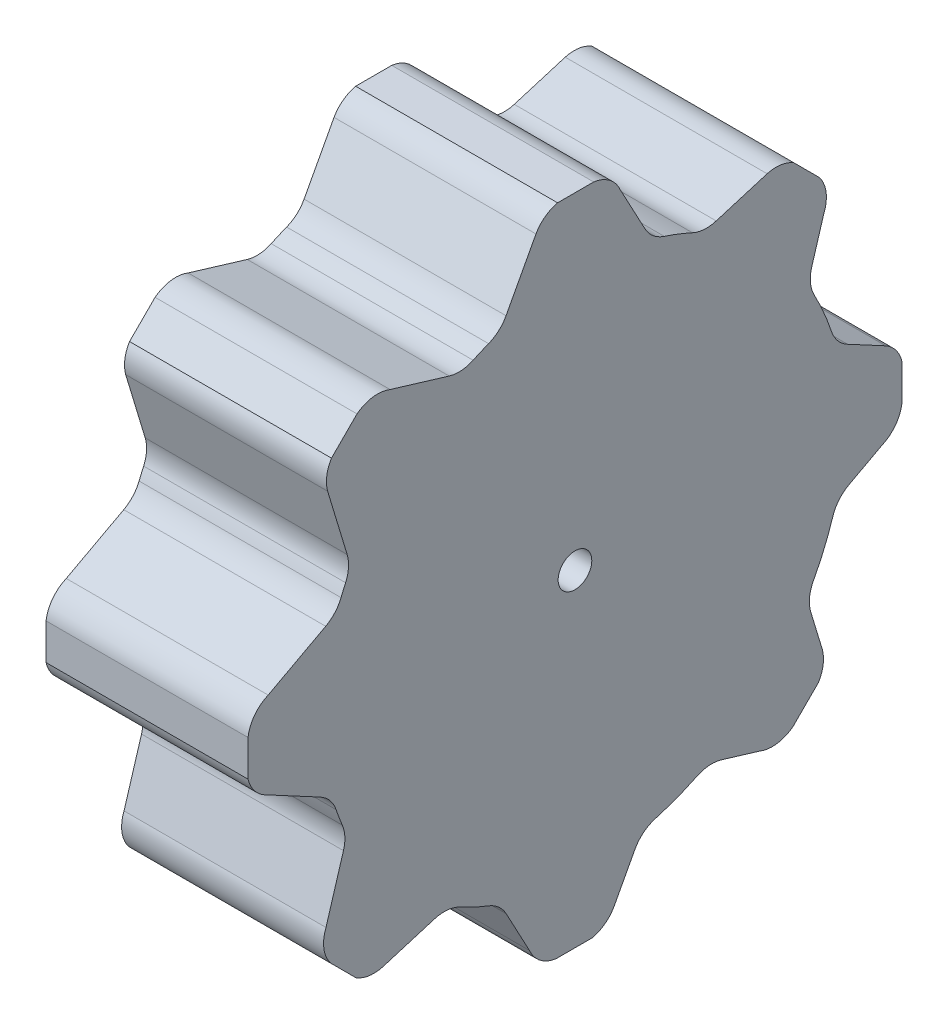
SolidWorks part; units mm, degrees
ref_plane "Front Plane" through (0, 0, 0) normal (0, 0, 1) x (1, 0, 0)
ref_plane "Top Plane" through (0, 0, 0) normal (0, 1, 0) x (1, 0, 0)
ref_plane "Right Plane" through (0, 0, 0) normal (1, 0, 0) x (0, 0, -1)
sketch "Sketch2" plane through (0, 0, 0) normal (1, 0, 0) x (0, 0, -1)
  line L4 (30.0857, -11.1861) -> (21.5417, -15.7633)
  line L5 (18.545, -19.7204) -> (18.545, -25.0855)
  line L6 (29.2555, -32.7457) -> (20.9479, -28.2952)
  line L7 (48.4288, 11.8388) -> (39.6545, 14.4915)
  line L11 (33.2739, -3.5445) -> (30.3732, 6.05)
  line L12 (34.7375, 13.8123) -> (30.9437, 10.0186)
  line L13 (77.5255, 16.2265) -> (73.8555, 23.0772)
  line L14 (56.8788, 15.3739) -> (61.3237, 23.671)
  line L15 (69.8985, 26.0738) -> (64.5333, 26.0738)
  line L16 (102.2913, -1.0523) -> (104.1103, 4.9644)
  line L17 (88.1041, 11.9586) -> (95.6688, 14.2456)
  line L18 (103.4312, 9.8814) -> (99.6374, 13.6751)
  line L19 (107.8316, -31.8426) -> (112.696, -29.2367)
  line L20 (107.6145, -13.6645) -> (113.2898, -16.7048)
  line L21 (115.6926, -25.2796) -> (115.6926, -19.9145)
  line L22 (88.8853, -57.7689) -> (94.5832, -59.4915)
  line L23 (102.1519, -45.3854) -> (103.8644, -51.05)
  line L24 (99.5002, -58.8123) -> (103.2939, -55.0186)
  line L25 (56.8883, -61.5554) -> (60.3821, -68.0772)
  line L26 (76.026, -62.8619) -> (72.914, -68.671)
  line L27 (64.3392, -71.0738) -> (69.7044, -71.0738)
  line L28 (32.7253, -41.3712) -> (30.1273, -49.9644)
  line L29 (46.2471, -56.9243) -> (38.5688, -59.2456)
  line L30 (30.8065, -54.8814) -> (34.6002, -58.6751)
  arc A2 (21.5417, -15.7633) -> (18.545, -19.7204) centre (23.5037, -20.3623) ccw
  arc A3 (18.545, -25.0855) -> (20.9479, -28.2952) centre (23.4133, -23.9453) ccw
  arc A5 (33.0415, -7.0564) -> (32.3654, -8.6398) centre (68.396, -23.0889) ccw
  arc A6 (39.6545, 14.4915) -> (34.7375, 13.8123) centre (37.7899, 9.8522) ccw
  arc A7 (30.9437, 10.0186) -> (30.3732, 6.05) centre (35.1924, 7.3825) ccw
  arc A8 (73.8555, 23.0772) -> (69.8985, 26.0738) centre (69.2566, 21.1152) ccw
  arc A9 (64.5333, 26.0738) -> (61.3237, 23.671) centre (65.6736, 21.2055) ccw
  arc A10 (104.1103, 4.9644) -> (103.4312, 9.8814) centre (99.471, 6.829) ccw
  arc A11 (99.6374, 13.6751) -> (95.6688, 14.2456) centre (97.0014, 9.4264) ccw
  arc A12 (112.696, -29.2367) -> (115.6926, -25.2796) centre (110.734, -24.6377) ccw
  arc A13 (115.6926, -19.9145) -> (113.2898, -16.7048) centre (110.8244, -21.0547) ccw
  arc A14 (94.5832, -59.4915) -> (99.5002, -58.8123) centre (96.4478, -54.8522) ccw
  arc A15 (103.2939, -55.0186) -> (103.8644, -51.05) centre (99.0453, -52.3825) ccw
  arc A16 (60.3821, -68.0772) -> (64.3392, -71.0738) centre (64.9811, -66.1152) ccw
  arc A17 (69.7044, -71.0738) -> (72.914, -68.671) centre (68.5641, -66.2055) ccw
  arc A18 (30.1273, -49.9644) -> (30.8065, -54.8814) centre (34.7666, -51.829) ccw
  arc A19 (34.6002, -58.6751) -> (38.5688, -59.2456) centre (37.2363, -54.4264) ccw
  arc A20 (54.2884, 13.0768) -> (51.989, 12.0934) centre (68.396, -23.0889) ccw
  arc A21 (84.5735, 12.1995) -> (80.3883, 13.8322) centre (68.396, -23.0889) ccw
  arc A22 (105.2312, -10.8354) -> (102.6637, -4.8486) centre (68.396, -23.0889) ccw
  arc A23 (102.5402, -41.5594) -> (105.4236, -34.7483) centre (68.396, -23.0889) ccw
  arc A24 (79.0599, -60.4154) -> (85.2656, -58.0517) centre (68.396, -23.0889) ccw
  arc A25 (50.0562, -57.3035) -> (54.2969, -59.2579) centre (68.396, -23.0889) ccw
  arc A26 (31.6299, -35.5483) -> (32.5555, -38.0033) centre (68.396, -23.0889) ccw
  arc A27 (29.2555, -32.7457) -> (31.6299, -35.5483) centre (26.8944, -37.1531) cw
  arc A28 (32.7253, -41.3712) -> (32.5555, -38.0033) centre (27.9392, -39.9243) ccw
  arc A29 (46.2471, -56.9243) -> (50.0562, -57.3035) centre (47.6941, -61.7103) cw
  arc A30 (56.8883, -61.5554) -> (54.2969, -59.2579) centre (52.4809, -63.9165) ccw
  arc A31 (76.026, -62.8619) -> (79.0599, -60.4154) centre (80.4334, -65.223) cw
  arc A32 (88.8853, -57.7689) -> (85.2656, -58.0517) centre (87.4384, -62.555) ccw
  arc A33 (102.1519, -45.3854) -> (102.5402, -41.5594) centre (106.9379, -43.9384) cw
  arc A34 (107.8316, -31.8426) -> (105.4236, -34.7483) centre (110.1927, -36.25) ccw
  arc A35 (107.6145, -13.6645) -> (105.2312, -10.8354) centre (109.9756, -9.2571) cw
  arc A36 (102.2913, -1.0523) -> (102.6637, -4.8486) centre (107.0774, -2.4993) ccw
  arc A37 (88.1041, 11.9586) -> (84.5735, 12.1995) centre (86.6572, 16.7446) cw
  arc A38 (77.5255, 16.2265) -> (80.3883, 13.8322) centre (81.9329, 18.5876) ccw
  arc A39 (56.8788, 15.3739) -> (54.2884, 13.0768) centre (52.4714, 17.735) cw
  arc A40 (48.4288, 11.8388) -> (51.989, 12.0934) centre (49.8758, 16.6249) ccw
  arc A41 (33.2739, -3.5445) -> (33.0415, -7.0564) centre (28.4878, -4.9914) cw
  arc A42 (30.0857, -11.1861) -> (32.3654, -8.6398) centre (27.7246, -6.7787) ccw
  circle A43 centre (67.1188, -22.5) radius 2.5
  point P95 (67.1188, -22.5)
  dimension "D3" = 5
  dimension "D1" = 5
  dimension "D2" = 8
extrude "Boss-Extrude2" add sketch "Sketch2" along normal blind 30 separate body
